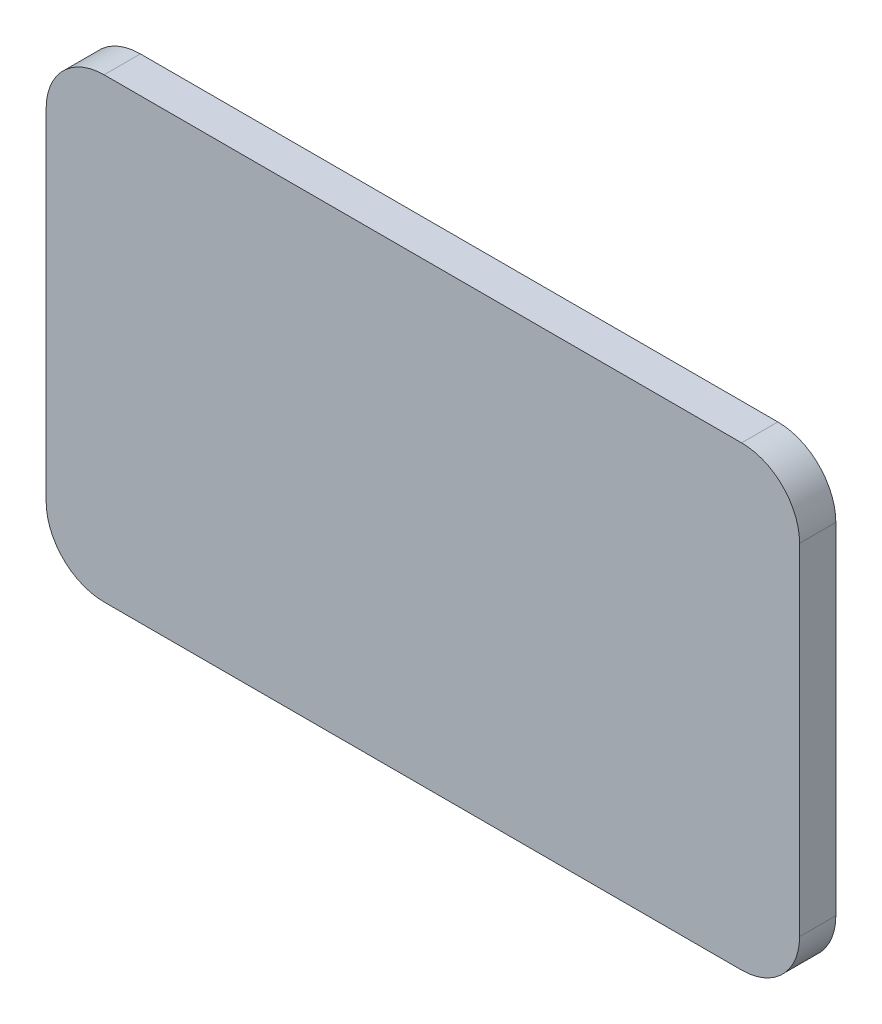
SolidWorks part; units mm, degrees
ref_plane "Plane1" through (0, 0, 0) normal (0, 0, 1) x (1, 0, 0)
ref_plane "Plane2" through (0, 0, 0) normal (0, 1, 0) x (1, 0, 0)
ref_plane "Plane3" through (0, 0, 0) normal (1, 0, 0) x (0, 0, -1)
sketch "Sketch1" plane through (0, 0, 0) normal (0, 0, 1) x (1, 0, 0)
  line L1 (13.96, -10) -> (-13.96, -10)
  line L2 (16.5, -7.46) -> (16.5, 7.46)
  line L3 (13.96, 10) -> (-13.96, 10)
  line L4 (-16.5, -7.46) -> (-16.5, 7.46)
  line L5 (16.5, -10) -> (-16.5, 10) construction
  line L6 (16.5, 10) -> (-16.5, -10) construction
  arc A0 (-13.96, -10) -> (-16.5, -7.46) centre (-13.96, -7.46) cw
  arc A1 (13.96, -10) -> (16.5, -7.46) centre (13.96, -7.46) ccw
  arc A2 (16.5, 7.46) -> (13.96, 10) centre (13.96, 7.46) ccw
  arc A3 (-13.96, 10) -> (-16.5, 7.46) centre (-13.96, 7.46) ccw
  point P0 (0, 0)
  dimension "D3" = 2.54
  dimension "D1" = 33
  dimension "D2" = 20
extrude "Boss-Extrude1" add sketch "Sketch1" along normal blind 1.5875
